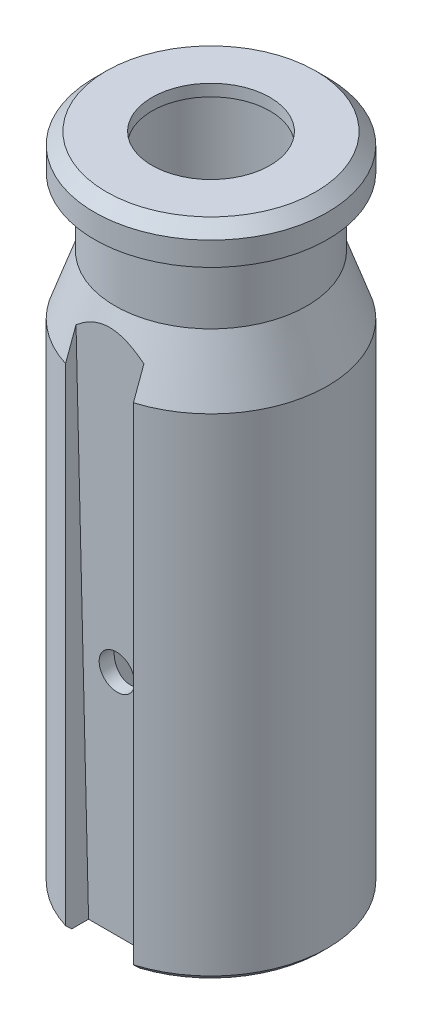
SolidWorks part; units mm, degrees
material "Chrome Stainless Steel"
ref_plane "Front Plane" through (0, 0, 0) normal (0, 0, 1) x (1, 0, 0)
ref_plane "Top Plane" through (0, 0, 0) normal (0, 1, 0) x (1, 0, 0)
ref_plane "Right Plane" through (0, 0, 0) normal (1, 0, 0) x (0, 0, -1)
sketch "MainBodyS" plane through (0, 0, 0) normal (0, 0, 1) x (1, 0, 0)
  line L1 (3.95, 0.2) -> (3.95, 16.7)
  line L2 (3.95, 16.7) -> (3.25, 18.7)
  line L3 (3.25, 18.7) -> (3.25, 21)
  line L4 (3.25, 21) -> (3.95, 21)
  line L5 (3.95, 21) -> (3.95, 21.8)
  line L6 (3.95, 21.8) -> (3.55, 22.2)
  line L7 (3.55, 22.2) -> (2, 22.2)
  line L8 (2, 22.2) -> (2, 21.8)
  line L9 (2, 21.8) -> (2.75, 21.8)
  line L10 (2.75, 21.8) -> (2.75, 4)
  line L11 (1.3, 0) -> (1.3, 4)
  line L12 (1.3, 4) -> (2.75, 4)
  line L13 (0, 0) -> (0, 22.2) construction
  line L14 (1.3, 0) -> (3.75, 0)
  line L15 (3.75, 0) -> (3.95, 0.2)
  dimension "D1" = 45
  dimension "D2" = 45
  dimension "D3" = 2.65
  dimension "D4" = 1.25
  dimension "D5" = 0.2
  dimension "D6" = 0.4
  dimension "D7" = 22.2
  dimension "D8" = 1.2
  dimension "D9" = 2.3
  dimension "D10" = 6.5
  dimension "D11" = 7.9
  dimension "D12" = 0.4
  dimension "D13" = 4
  dimension "D14" = 4
  dimension "D15" = 2.6
  dimension "D16" = 2
  dimension "D17" = 5.5
  dimension "D18" = 3.5
  dimension "D19" = 0.75
  dimension "D20" = 0.5
revolve "MAIN BODY" add sketch "MainBodyS" angle 360 about L13
ref_plane "SLOT END PLANE" through (0, 18.7, 0) normal (0, -1, 0) x (-1, 0, 0)
sketch "LoftedSlotStartS" plane through (0, 0, 0) normal (0, -1, 0) x (-1, 0, 0)
  line L0 (0, 0) -> (0, 3.475) construction
  line L1 (-1.15, 3.95) -> (1.15, 3.95)
  line L2 (-1.15, 3.95) -> (-1.15, 3)
  line L3 (-1.15, 3) -> (1.15, 3)
  line L4 (1.15, 3.95) -> (1.15, 3)
  line L5 (-1.15, 3.95) -> (1.15, 3) construction
  line L6 (-1.15, 3) -> (1.15, 3.95) construction
  circle A0 centre (0, 0) radius 3.95 construction
  point P0 (0, 3.475)
  dimension "D1" = 0.95
  dimension "D2" = 2.3
  dimension "D3" = 3
sketch "LoftedSlotEndS" plane through (0, 18.7, 0) normal (0, -1, 0) x (-1, 0, 0)
  line L1 (-1.15, 3.95) -> (1.15, 3.95)
  line L2 (-1.15, 3.95) -> (-1.15, 3.45)
  line L3 (-1.15, 3.45) -> (1.15, 3.45)
  line L4 (1.15, 3.95) -> (1.15, 3.45)
  line L5 (-1.15, 3.95) -> (1.15, 3.45) construction
  line L6 (-1.15, 3.45) -> (1.15, 3.95) construction
  point P0 (0, 3.7)
  dimension "D1" = 0.5
loft "LOFTED SLOT" cut profiles "LoftedSlotEndS", "LoftedSlotStartS"
mirror "LS HM" about plane through (0, 0, 0) normal (0, 0, 1) of "LOFTED SLOT"
sketch "LocatingHoleS" plane through (0, -0.0722, 2.9983) normal (0, -0.0241, 0.9997) x (1, 0, 0)
  line L0 (0, 0) -> (0, 8) construction
  circle A0 centre (0, 8) radius 0.6
  dimension "D1" = 1.2
  dimension "D2" = 8
extrude "LOCATING HOLE" cut sketch "LocatingHoleS" against normal up to next
